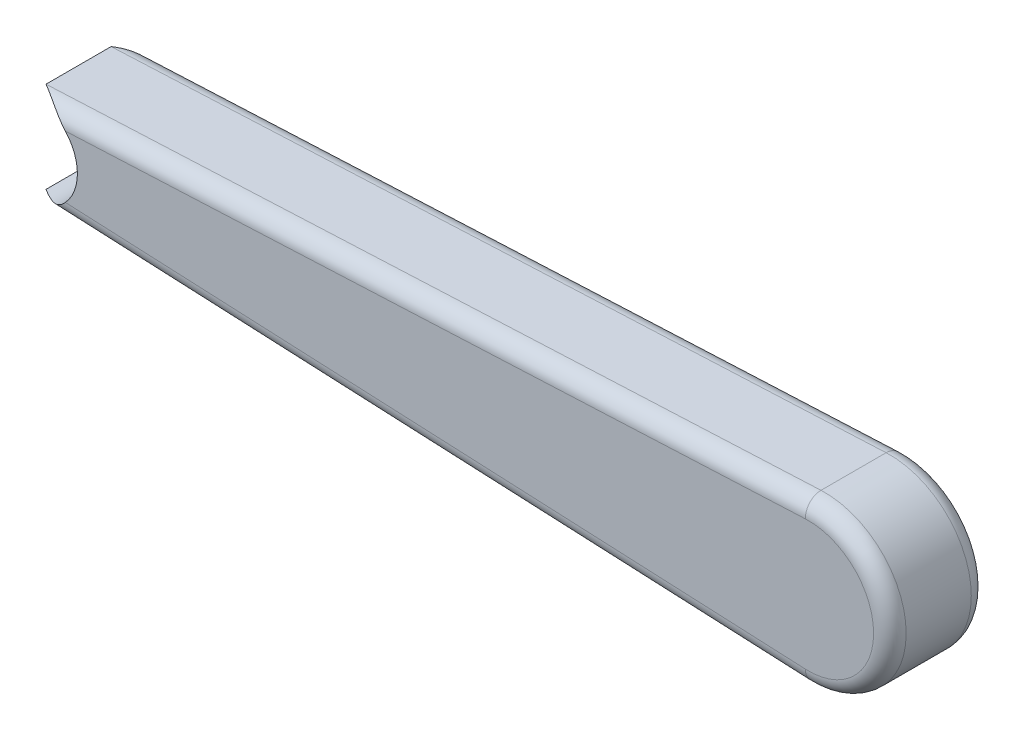
SolidWorks part; units mm, degrees
ref_plane "Front Plane" through (0, 0, 0) normal (0, 0, 1) x (1, 0, 0)
ref_plane "Top Plane" through (0, 0, 0) normal (0, 1, 0) x (1, 0, 0)
ref_plane "Right Plane" through (0, 0, 0) normal (1, 0, 0) x (0, 0, -1)
sketch "Sketch1" plane through (0, 0, 0) normal (0, 0, 1) x (1, 0, 0)
  line L0 (-59.3623, 0) -> (59.8877, 0) construction
  line L1 (-59.6852, 6.9926) -> (59.8877, 12.5133)
  line L2 (59.8877, -12.5133) -> (-59.6852, -6.9926)
  circle A0 centre (-59.3623, 0) radius 7
  circle A1 centre (59.8877, 0) radius 12.5
  dimension "D2" = 14
  dimension "D3" = 25
  dimension "D1" = 119.25
extrude "Boss-Extrude1" add sketch "Sketch1" along normal blind 15
sketch "Sketch2" plane through (0, 0, 0) normal (0, 0, -1) x (-1, 0, 0)
  circle A0 centre (-59.8877, 0) radius 5
  dimension "D1" = 10
extrude "Cut-Extrude1" cut sketch "Sketch2" against normal blind 10
fillet "Fillet1" radius 2.5 6 edges at (-0.187, -9.7396, 15) (72.3877, 0, 15) (-0.187, -9.7396, 0) (72.3877, 0, 0) (-0.187, 9.7396, 15) (-0.187, 9.7396, 0)
